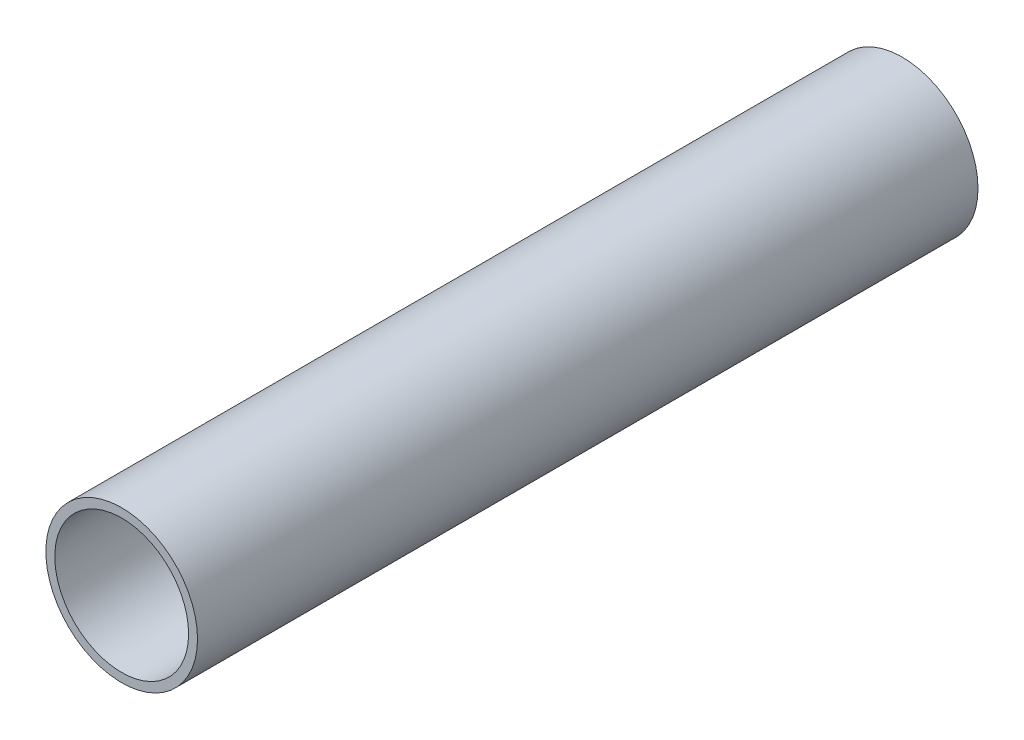
SolidWorks part; units mm, degrees
ref_plane "Front Plane" through (0, 0, 0) normal (0, 0, 1) x (1, 0, 0)
ref_plane "Top Plane" through (0, 0, 0) normal (0, 1, 0) x (1, 0, 0)
ref_plane "Right Plane" through (0, 0, 0) normal (1, 0, 0) x (0, 0, -1)
sketch "Sketch1" plane through (0, 0, 0) normal (0, 0, 1) x (1, 0, 0)
  circle A0 centre (0, 0) radius 15
  circle A1 centre (0, 0) radius 17
  dimension "D1" = 30
  dimension "D2" = 2
extrude "Boss-Extrude1" add sketch "Sketch1" along normal mid plane 175 contours A1 A0
